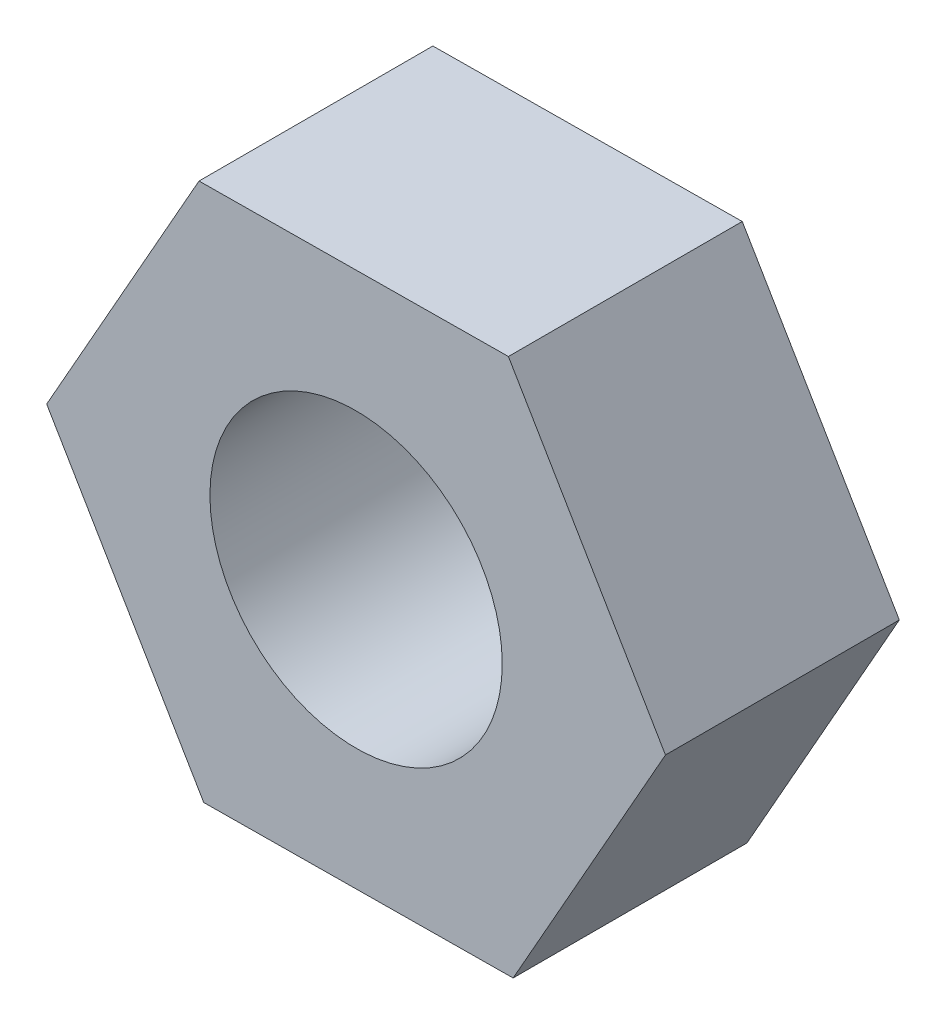
SolidWorks part; units mm, degrees
ref_plane "前视基准面" through (0, 0, 0) normal (0, 0, 1) x (1, 0, 0)
ref_plane "上视基准面" through (0, 0, 0) normal (0, 1, 0) x (1, 0, 0)
ref_plane "右视基准面" through (0, 0, 0) normal (1, 0, 0) x (0, 0, -1)
sketch "草图1" plane through (0, 0, 0) normal (0, 0, 1) x (1, 0, 0)
  line L1 (1.6119, -2.7359) -> (3.1753, 0.028)
  line L2 (3.1753, 0.028) -> (1.5634, 2.7639)
  line L3 (1.5634, 2.7639) -> (-1.6119, 2.7359)
  line L4 (-1.6119, 2.7359) -> (-3.1753, -0.028)
  line L5 (-3.1753, -0.028) -> (-1.5634, -2.7639)
  line L6 (-1.5634, -2.7639) -> (1.6119, -2.7359)
  circle A0 centre (0, 0) radius 2.75 construction
  circle A1 centre (0, 0) radius 1.5
extrude "凸台-拉伸1" add sketch "草图1" along normal blind 2.4
